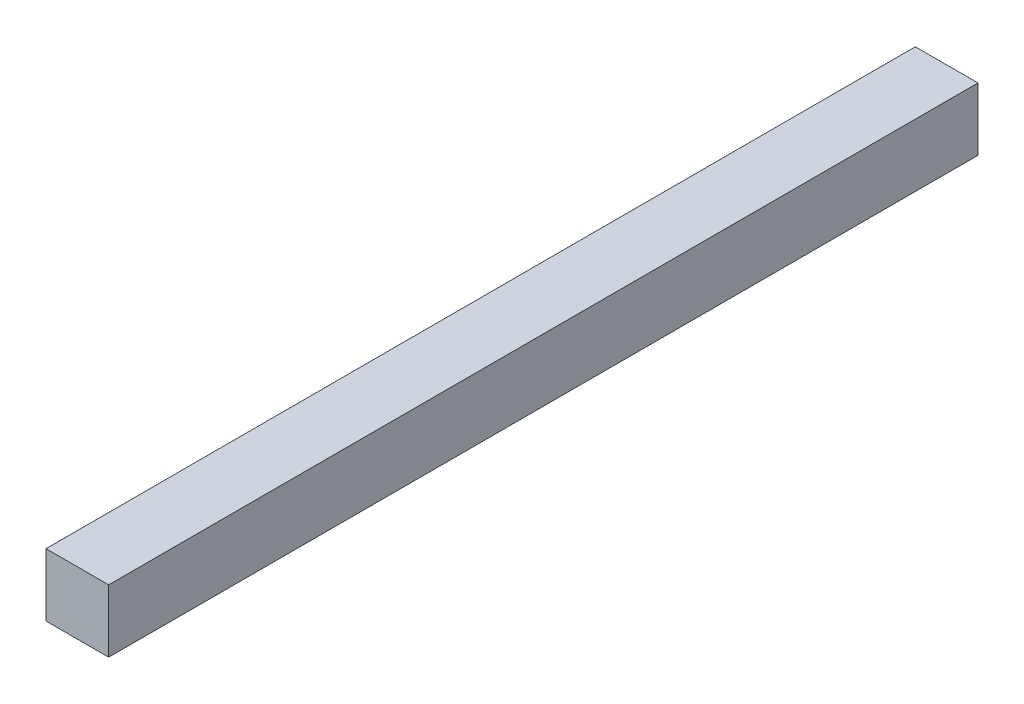
SolidWorks part; units mm, degrees
ref_plane "Plan de face" through (0, 0, 0) normal (0, 0, 1) x (1, 0, 0)
ref_plane "Plan de dessus" through (0, 0, 0) normal (0, 1, 0) x (1, 0, 0)
ref_plane "Plan de droite" through (0, 0, 0) normal (1, 0, 0) x (0, 0, -1)
sketch "Esquisse1" plane through (0, 0, 0) normal (0, 0, 1) x (1, 0, 0)
  line L1 (0, 0) -> (62, 0)
  line L2 (0, 0) -> (0, 62)
  line L3 (0, 62) -> (62, 62)
  line L4 (62, 0) -> (62, 62)
  dimension "D1" = 62
  dimension "D2" = 62
extrude "Boss.-Extru.1" add sketch "Esquisse1" along normal blind 860
sketch "Esquisse2" plane through (0, 0, 0) normal (0, 0, 1) x (1, 0, 0)
  line L0 (0, 31) -> (62, 31) construction
  line L1 (0, 62) -> (0, 0) construction
  line L2 (62, 0) -> (62, 62) construction
  circle A0 centre (31, 31) radius 6
  dimension "D1" = 12
extrude "Enlèv. mat.-Extru.1" cut sketch "Esquisse2" along normal blind 80
